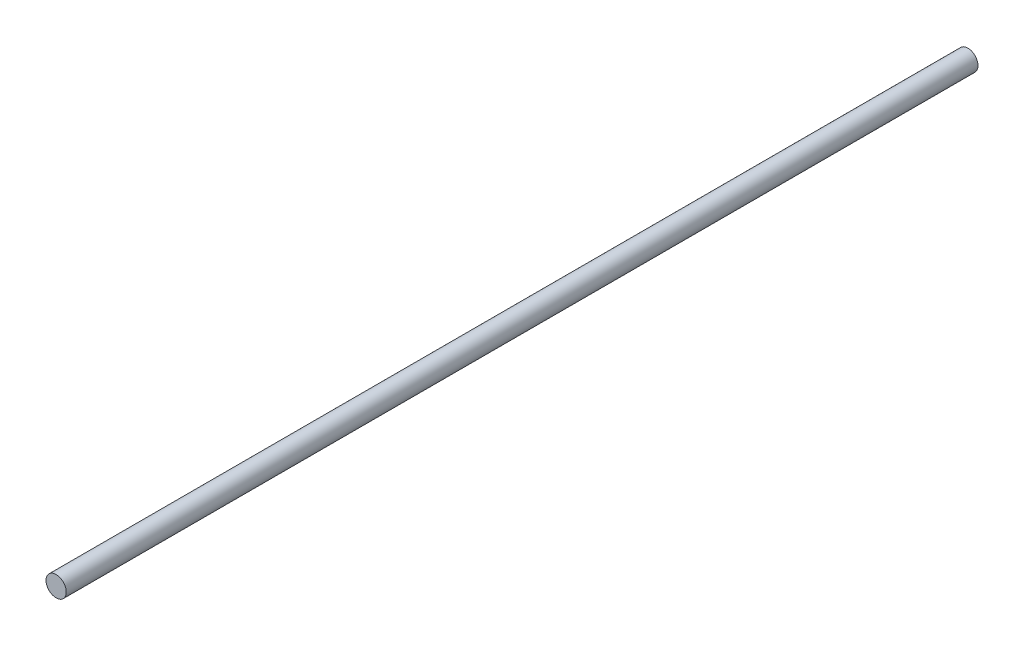
SolidWorks part; units mm, degrees
ref_plane "Front Plane" through (0, 0, 0) normal (0, 0, 1) x (1, 0, 0)
ref_plane "Top Plane" through (0, 0, 0) normal (0, 1, 0) x (1, 0, 0)
ref_plane "Right Plane" through (0, 0, 0) normal (1, 0, 0) x (0, 0, -1)
sketch "Sketch1" plane through (0, 0, 0) normal (0, 0, 1) x (1, 0, 0)
  circle A0 centre (0, 0) radius 1
  dimension "D1" = 2
extrude "Boss-Extrude1" add sketch "Sketch1" along normal blind 90
